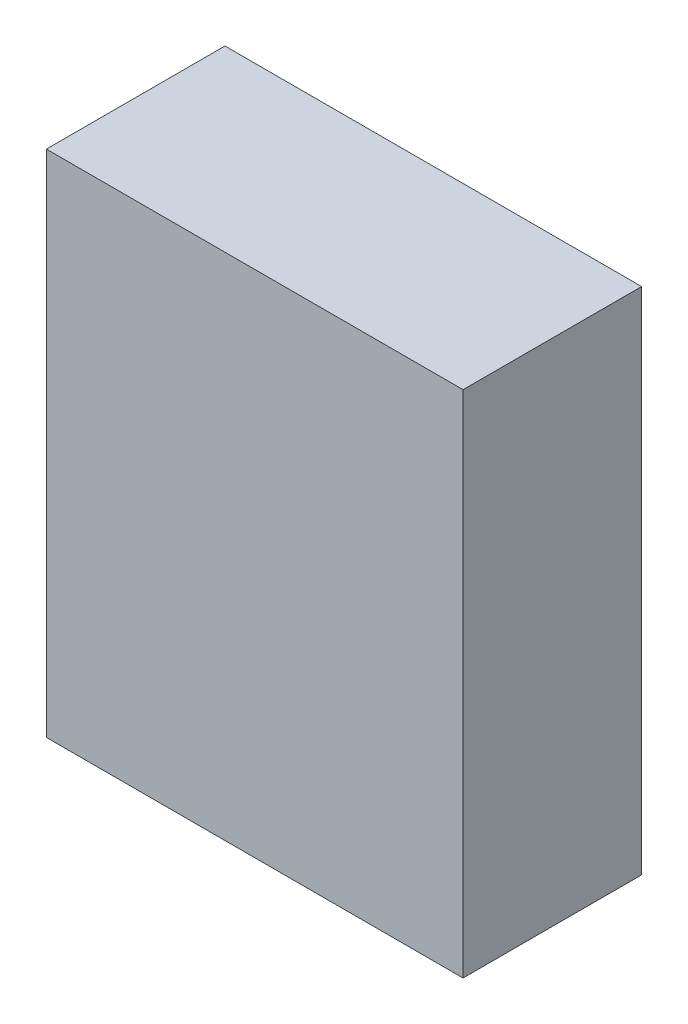
SolidWorks part; units mm, degrees
ref_plane "Front Plane" through (0, 0, 0) normal (0, 0, 1) x (1, 0, 0)
ref_plane "Top Plane" through (0, 0, 0) normal (0, 1, 0) x (1, 0, 0)
ref_plane "Right Plane" through (0, 0, 0) normal (1, 0, 0) x (0, 0, -1)
sketch "Sketch1" plane through (0, 0, 0) normal (0, 1, 0) x (1, 0, 0)
  line L1 (0, 0) -> (88.9, 0)
  line L2 (0, 0) -> (0, 38.1)
  line L3 (0, 38.1) -> (88.9, 38.1)
  line L4 (88.9, 0) -> (88.9, 38.1)
  dimension "D1" = 88.9
  dimension "D2" = 38.1
extrude "Boss-Extrude1" add sketch "Sketch1" along normal blind 108.712
